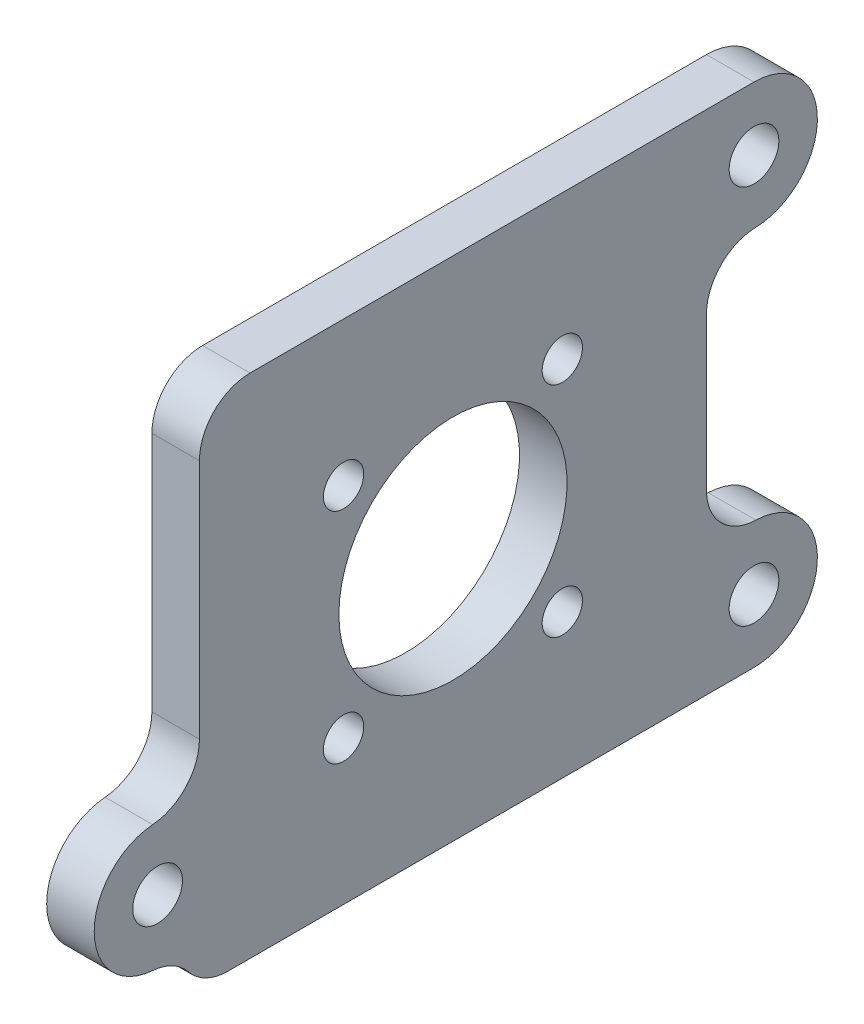
SolidWorks part; units mm, degrees
material "6061-T6 (SS)"
ref_plane "Front Plane" through (0, 0, 0) normal (0, 0, 1) x (1, 0, 0)
ref_plane "Top Plane" through (0, 0, 0) normal (0, 1, 0) x (1, 0, 0)
ref_plane "Right Plane" through (0, 0, 0) normal (1, 0, 0) x (0, 0, -1)
sketch "Sketch1" plane through (0, 0, 0) normal (1, 0, 0) x (0, 0, -1)
  line L0 (-25.4, 25.4) -> (-25.4, -3.8446)
  line L1 (-25.4, 25.4) -> (25.4, 25.4)
  line L2 (-25.4, -25.4) -> (25.4, -25.4)
  line L3 (25.4, 25.4) -> (25.4, -25.4) construction
  line L4 (25.4, 25.4) -> (-25.4, -25.4) construction
  line L5 (25.4, 25.4) -> (30.1625, 25.4)
  line L6 (25.4, 7.6244) -> (25.4, -7.6244)
  line L7 (25.4, -25.4) -> (30.1625, -25.4)
  line L9 (-25.4, -25.4) -> (-25.5525, -25.4)
  circle A0 centre (0, 0) radius 11.43
  arc A1 (30.3389, 12.7025) -> (30.1625, 25.4) centre (30.1625, 19.05) ccw
  arc A2 (25.4, 7.6244) -> (30.3389, 12.7025) centre (30.48, 7.6244) cw
  arc A3 (25.4, -7.6244) -> (30.3389, -12.7025) centre (30.48, -7.6244) ccw
  arc A4 (30.1625, -25.4) -> (30.3389, -12.7025) centre (30.1625, -19.05) ccw
  arc A5 (-30.0849, -8.9092) -> (-30.0849, -21.5708) centre (-29.591, -15.24) ccw
  arc A6 (-30.0849, -8.9092) -> (-25.4, -3.8446) centre (-30.48, -3.8446) ccw
  arc A7 (-30.0849, -21.5708) -> (-25.5525, -25.4) centre (-30.48, -26.6354) cw
  dimension "D1" = 50.8
  dimension "D2" = 22.86
  dimension "D3" = 12.7
  dimension "D5" = 5.08
  dimension "D6" = 4.191
  dimension "D7" = 15.24
  dimension "D4" = 4.7625
extrude "Boss-Extrude1" add sketch "Sketch1" along normal blind 4.7625
hole_wizard "#10-32 Tapped Hole1" positions "Sketch2" profile "Sketch3" tap size "#10-32" standard "ANSI Inch" end condition through all
sketch "Sketch2" plane through (4.7625, 0, 0) normal (1, 0, 0) x (0, 0, -1)
  line L0 (-10.9601, -10.9601) -> (10.9601, -10.9601)
  line L1 (-10.9601, -10.9601) -> (-10.9601, 10.9601)
  line L2 (10.9601, -10.9601) -> (10.9601, 10.9601)
  line L3 (-10.9601, 10.9601) -> (10.9601, 10.9601)
  line L4 (10.9601, 10.9601) -> (-10.9601, -10.9601) construction
  point P0 (-10.9601, 10.9601)
  point P4 (-10.9601, -10.9601)
  point P5 (10.9601, -10.9601)
  point P32 (10.9601, 10.9601)
  dimension "D1" = 21.9202
sketch "Sketch3" plane through (4.7625, 10.9601, 10.9601) normal (0, 1, 0) x (0, 0, -1)
  line L0 (0, 0) -> (0, 4.7625)
  line L1 (0, 4.7625) -> (2.0193, 4.7625)
  line L2 (2.0193, 4.7625) -> (2.0193, 0)
  line L5 (2.0193, 0) -> (0, 0)
  line L11 (0, -6.35) -> (0, 107.95) construction
  dimension "Thru Tap Drill Dia." = 4.0386
  dimension "Thru Tap Drill Depth" = 4.7625
cosmetic thread "Hole Thread1" parameters "D1"=3.048, "D2"=5.0386
cosmetic thread "Hole Thread2" parameters "D1"=3.048, "D2"=5.0386
cosmetic thread "Hole Thread3" parameters "D1"=3.048, "D2"=5.0386
cosmetic thread "Hole Thread4" parameters "D1"=3.048, "D2"=5.0386
hole_wizard "#10 Clearance Hole1" positions "Sketch4" profile "Sketch5" hole size "#10" standard "ANSI Inch" end condition through all
sketch "Sketch4" plane through (4.7625, 0, 0) normal (1, 0, 0) x (0, 0, -1)
  point P0 (-29.591, -15.24)
  point P3 (30.1625, 19.05)
  point P6 (30.1625, -19.05)
sketch "Sketch5" plane through (4.7625, -15.24, 29.591) normal (0, 1, 0) x (0, 0, -1)
  line L0 (0, 0) -> (0, 4.7625)
  line L1 (0, 4.7625) -> (2.4892, 4.7625)
  line L2 (2.4892, 4.7625) -> (2.4892, 0)
  line L5 (2.4892, 0) -> (0, 0)
  line L11 (0, -6.35) -> (0, 107.95) construction
  dimension "Thru Hole Dia." = 4.9784
  dimension "Thru Hole Depth" = 4.7625
fillet "Fillet1" radius 5.08 2 edges at (2.3813, 25.4, 25.4) (2.3813, -25.4, 25.5525)
sketch "Sketch6" plane through (4.7625, 0, 0) normal (1, 0, 0) x (0, 0, -1)
  line L1 (-56.2295, -23.7959) -> (-70.9407, -23.7959)
  line L2 (-56.2295, -23.7959) -> (-56.2295, -7.8666)
  line L3 (-56.2295, -7.8666) -> (-70.9407, -7.8666)
  line L4 (-70.9407, -23.7959) -> (-70.9407, -7.8666)
  line L5 (-56.2295, -23.7959) -> (-70.9407, -7.8666) construction
  line L6 (-56.2295, -7.8666) -> (-70.9407, -23.7959) construction
  point P4 (-63.5851, -15.8313)
extrude "Boss-Extrude2" [suppressed] add sketch "Sketch6" against normal up to surface (4.7625 mm away) separate body
sketch "Sketch7" [suppressed] plane through (0, 0, 0) normal (-1, 0, 0) x (0, 0, 1)
  line L0 (4.1979, -25.4) -> (-11.0421, -25.4)
  line L1 (4.1979, -25.4) -> (4.1979, -36.6821)
  line L2 (-11.0421, -25.4) -> (-11.0421, -36.6821)
  line L3 (4.1979, -36.6821) -> (-11.0421, -36.6821)
  line L4 (22.5213, -25.4) -> (-30.1625, -25.4) construction
  line L5 (-12.2807, 25.4) -> (2.9593, 25.4)
  line L6 (-12.2807, 25.4) -> (-12.2807, 34.9029)
  line L7 (2.9593, 25.4) -> (2.9593, 34.9029)
  line L8 (-12.2807, 34.9029) -> (2.9593, 34.9029)
  line L9 (-30.1625, 25.4) -> (20.32, 25.4) construction
  dimension "D1" = 15.24
extrude "Boss-Extrude3" [suppressed] add sketch "Sketch7" against normal blind 1.524
hole_wizard "CSK for #6 Flat Head Machine Screw (100)1" positions "3DSketch1" profile "Sketch8" countersink size "#6" standard "ANSI Inch"
sketch3d "3DSketch1"
  line L0 (0, -10.9601, 10.9601) -> (4.7625, -10.9601, 10.9601) construction
  line L1 (0, -10.9601, -10.9601) -> (4.7625, -10.9601, -10.9601) construction
  line L2 (0, 10.9601, -10.9601) -> (4.7625, 10.9601, -10.9601) construction
  line L3 (0, 10.9601, 10.9601) -> (4.7625, 10.9601, 10.9601) construction
  circle A0 centre (0, 10.9601, -10.9601) radius 2.0193 construction
  circle A1 centre (0, 10.9601, 10.9601) radius 2.0193 construction
  point P0 (0, 11.9348, -9.1916)
  point P4 (2.0193, 10.9601, -10.9601)
  point P5 (0, 12.0813, 12.6395)
  point P9 (2.0193, 10.9601, 10.9601)
  point P10 (0, -10.9601, 10.9601)
  point P14 (0, -10.9601, -10.9601)
  point P18 (0, 10.9601, -10.9601)
  point P22 (0, 10.9601, 10.9601)
sketch "Sketch8" plane through (0, 10.9601, 10.9601) normal (0, 1, 0) x (0, 0, 1)
  line L0 (0, 0) -> (0, 4.7625)
  line L1 (0, 4.7625) -> (1.8986, 4.7625)
  line L2 (1.8986, 4.7625) -> (1.8986, 1.38)
  line L3 (1.8986, 1.38) -> (3.5433, 0)
  line L5 (3.5433, 0) -> (0, 0)
  line L6 (-1.8986, 1.38) -> (-3.5433, 0) construction
  line L11 (0, -6.35) -> (0, 107.95) construction
  dimension "Thru Hole Dia." = 3.7973
  dimension "Thru Hole Depth" = 4.7625
  dimension "Near C'Sink Dia." = 7.0866
  dimension "Near C'Sink Angle" = 100
